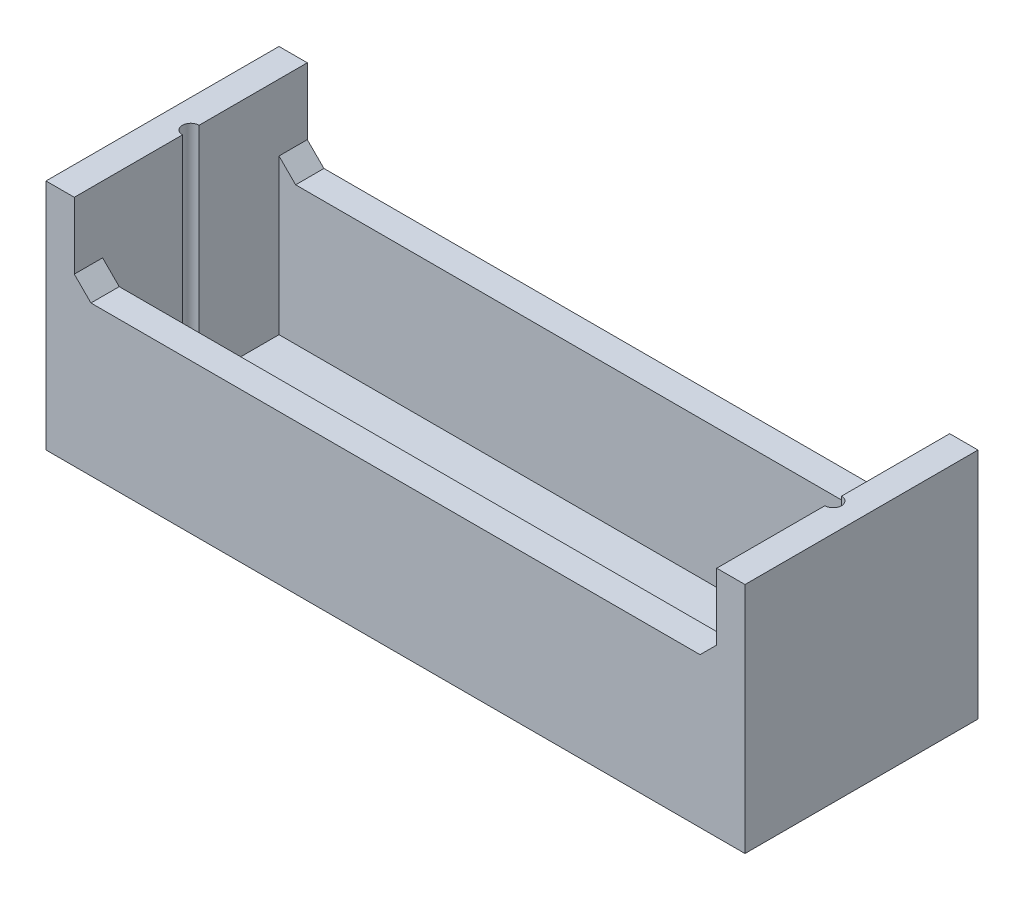
SolidWorks part; units mm, degrees
ref_plane "Front Plane" through (0, 0, 0) normal (0, 0, 1) x (1, 0, 0)
ref_plane "Top Plane" through (0, 0, 0) normal (0, 1, 0) x (1, 0, 0)
ref_plane "Right Plane" through (0, 0, 0) normal (1, 0, 0) x (0, 0, -1)
sketch "Sketch1" plane through (0, 0, 0) normal (0, 1, 0) x (1, 0, 0)
  line L0 (-2, 12) -> (40, 12)
  line L1 (0, 0) -> (38, 0) construction
  line L2 (0, 0) -> (0, 10) construction
  line L3 (0, 10) -> (38, 10) construction
  line L4 (38, 0) -> (38, 10) construction
  line L5 (40, -2) -> (40, 12)
  line L6 (-2, -2) -> (40, -2)
  line L7 (-2, -2) -> (-2, 12)
  dimension "D1" = 10
  dimension "D2" = 38
  dimension "D3" = 2
extrude "Boss-Extrude1" add sketch "Sketch1" along normal blind 10
shell "Shell1" thickness 1.7
sketch "Sketch2" plane through (0, 10, 0) normal (0, 1, 0) x (1, 0, 0)
  line L0 (-2, -2) -> (40, -2) construction
  line L1 (-2, 12) -> (-0.3, 12)
  line L2 (-2, 12) -> (-2, -2)
  line L3 (-2, -2) -> (-0.3, -2)
  line L4 (-0.3, 12) -> (-0.3, -2)
  line L5 (40, -2) -> (40, 12) construction
  line L6 (40, 12) -> (38.3, 12)
  line L7 (40, 12) -> (40, -2)
  line L8 (40, -2) -> (38.3, -2)
  line L9 (38.3, 12) -> (38.3, -2)
  line L10 (40, 12) -> (-2, 12) construction
  line L11 (-0.3, 10.3) -> (-0.3, -0.3) construction
  line L12 (38.3, -0.3) -> (38.3, 10.3) construction
extrude "Boss-Extrude2" add sketch "Sketch2" along normal blind 5
sketch "Sketch3" plane through (0, 15, 0) normal (0, 1, 0) x (1, 0, 0)
  line L0 (-2, 5) -> (40, 5) construction
  line L1 (-2, 12) -> (-2, -2) construction
  line L2 (40, -2) -> (40, 12) construction
  line L3 (-0.3, 10.3) -> (-0.3, -0.3) construction
  line L6 (38.3, 12) -> (38.3, -2) construction
  circle A0 centre (-0.3, 5) radius 0.5
  circle A1 centre (38.3, 5) radius 0.5
  point P12 (0, 0)
  dimension "D1" = 1
extrude "Cut-Extrude1" cut sketch "Sketch3" against normal up to surface (13.3 mm away) up to face at (19, 1.7, -5)
chamfer "Chamfer1" distance 1 angle 45 4 edges at (38.3, 10, 1.15) (38.3, 10, -11.15) (-0.3, 10, -11.15) (-0.3, 10, 1.15)
chamfer "Chamfer2" distance 1 angle 45 4 edges at (19, 0, 2) (40, 0, -5) (19, 0, -12) (-2, 0, -5)
